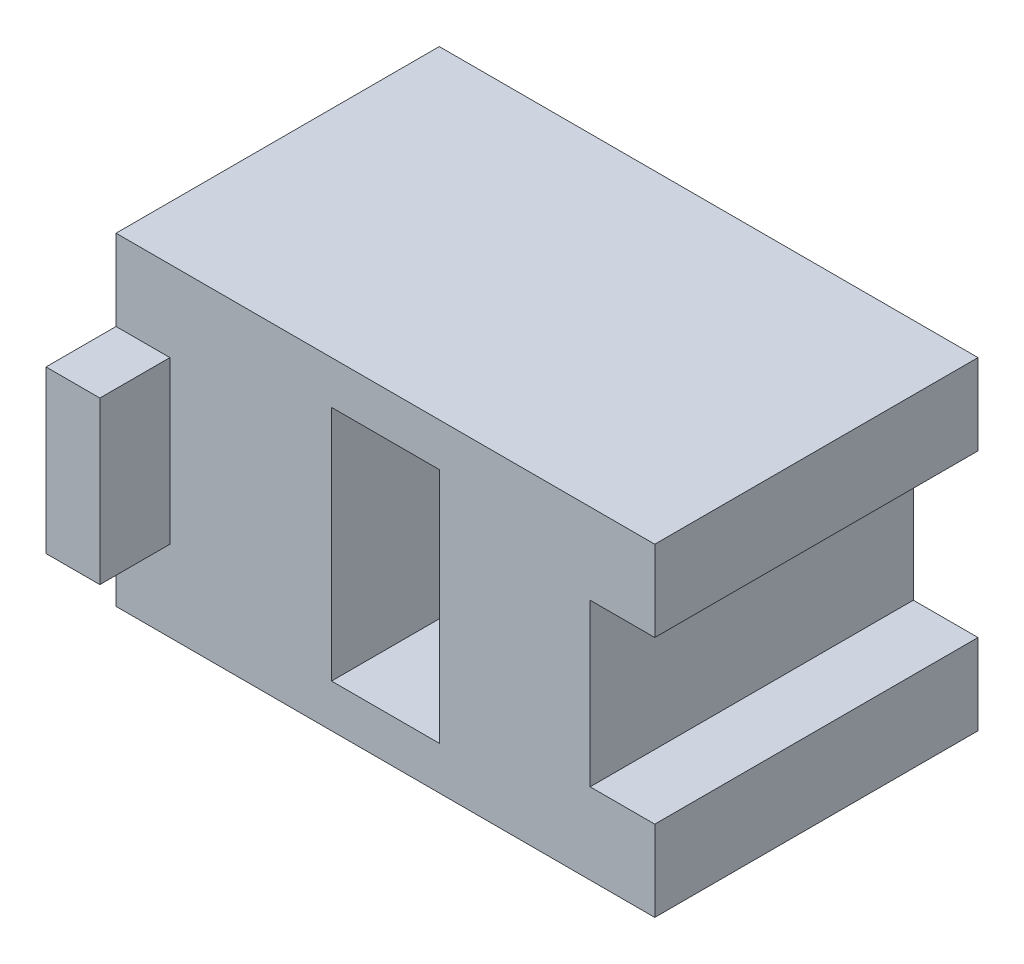
SolidWorks part; units mm, degrees
ref_plane "Спереди" through (0, 0, 0) normal (0, 0, 1) x (1, 0, 0)
ref_plane "Сверху" through (0, 0, 0) normal (0, 1, 0) x (1, 0, 0)
ref_plane "Справа" through (0, 0, 0) normal (1, 0, 0) x (0, 0, -1)
sketch "Эскиз1" plane through (0, 0, 0) normal (0, 0, 1) x (1, 0, 0)
  line L1 (-25, -15) -> (25, -15)
  line L2 (-25, -15) -> (-25, 15)
  line L3 (-25, 15) -> (25, 15)
  line L4 (25, -15) -> (25, 15)
  line L5 (-25, -15) -> (25, 15) construction
  line L6 (-25, 15) -> (25, -15) construction
  point P0 (0, 0)
  dimension "D1" = 30
  dimension "D2" = 50
extrude "Бобышка-Вытянуть1" add sketch "Эскиз1" along normal blind 30
sketch "Эскиз2" plane through (0, 0, 30) normal (0, 0, 1) x (1, 0, 0)
  line L0 (0, 15) -> (0, -15) construction
  line L1 (25, 15) -> (-25, 15) construction
  line L2 (-25, -15) -> (25, -15) construction
  line L3 (25, -15) -> (25, 15) construction
  line L4 (-5, -11) -> (5, -11)
  line L5 (-5, -11) -> (-5, 11)
  line L6 (-5, 11) -> (5, 11)
  line L7 (5, -11) -> (5, 11)
  line L8 (-5, -11) -> (5, 11) construction
  line L9 (-5, 11) -> (5, -11) construction
  line L10 (19, -7.5) -> (25, -7.5)
  line L11 (19, -7.5) -> (19, 7.5)
  line L12 (19, 7.5) -> (25, 7.5)
  line L13 (25, -7.5) -> (25, 7.5)
  line L14 (19, -7.5) -> (25, 7.5) construction
  line L15 (19, 7.5) -> (25, -7.5) construction
  point P6 (0, 0)
  point P12 (22, 0)
  dimension "D1" = 4
  dimension "D2" = 10
  dimension "D3" = 15
  dimension "D4" = 6
extrude "Вырез-Вытянуть1" cut sketch "Эскиз2" against normal through all
sketch "Эскиз3" plane through (0, 0, 30) normal (0, 0, 1) x (1, 0, 0)
  line L1 (-20, -7.5) -> (-25, -7.5)
  line L2 (-20, -7.5) -> (-20, 7.5)
  line L3 (-20, 7.5) -> (-25, 7.5)
  line L4 (-25, -7.5) -> (-25, 7.5)
  line L5 (-20, -7.5) -> (-25, 7.5) construction
  line L6 (-20, 7.5) -> (-25, -7.5) construction
  line L7 (25, 7.5) -> (19, 7.5) construction
  line L9 (-25, 15) -> (-25, -15) construction
  point P0 (-22.5, 0)
  dimension "D1" = 5
extrude "Бобышка-Вытянуть2" add sketch "Эскиз3" along normal blind 6.5
sketch "Эскиз4" plane through (0, 0, 0) normal (0, 1, 0) x (1, 0, 0)
  line L0 (-25, 0) -> (-25, 5)
  line L1 (-25, 5) -> (-5, 0)
  line L2 (25, 0) -> (-25, 0) construction
  line L3 (-5, 0) -> (-25, 0)
  dimension "D1" = 20
  dimension "D2" = 5
extrude "Бобышка-Вытянуть3" add sketch "Эскиз4" along normal blind 6 and the other way blind 6
